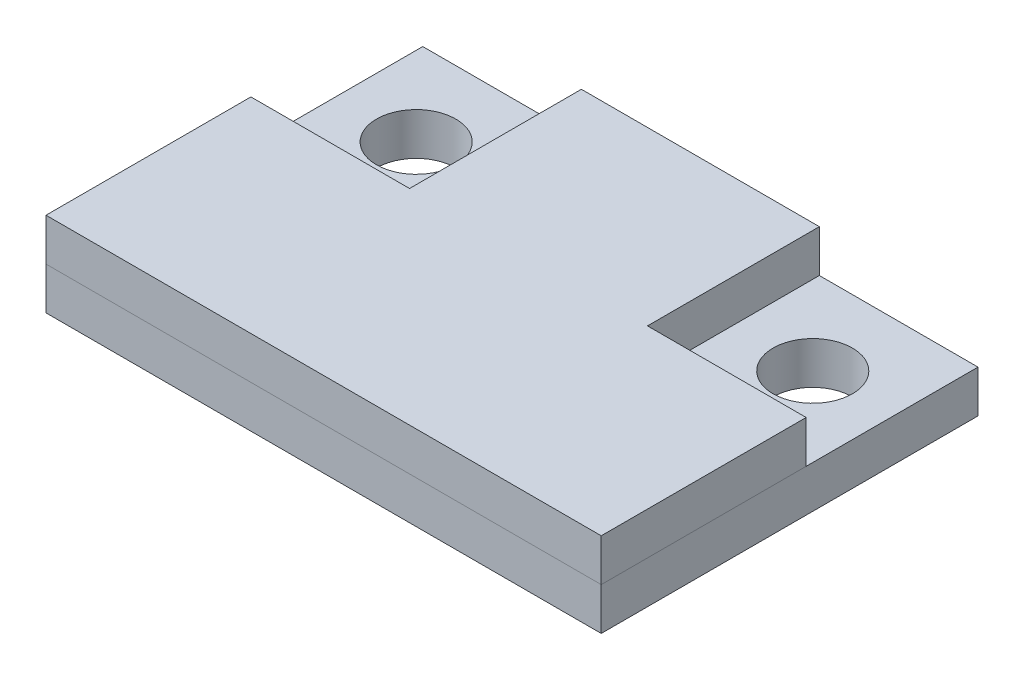
SolidWorks part; units mm, degrees
ref_plane "Front Plane" through (0, 0, 0) normal (0, 0, 1) x (1, 0, 0)
ref_plane "Top Plane" through (0, 0, 0) normal (0, 1, 0) x (1, 0, 0)
ref_plane "Right Plane" through (0, 0, 0) normal (1, 0, 0) x (0, 0, -1)
sketch "Sketch1" plane through (0, 0, 0) normal (0, 1, 0) x (1, 0, 0)
  line L0 (7.5, 3.875) -> (-7.5, 3.875) construction
  line L1 (-10.5, -7.125) -> (10.5, -7.125)
  line L2 (-10.5, -7.125) -> (-10.5, 7.125)
  line L3 (-10.5, 7.125) -> (10.5, 7.125)
  line L4 (10.5, -7.125) -> (10.5, 7.125)
  line L5 (-10.5, -7.125) -> (10.5, 7.125) construction
  line L6 (-10.5, 7.125) -> (10.5, -7.125) construction
  line L7 (0, 0) -> (0, 3.875) construction
  circle A0 centre (-7.5, 3.875) radius 1.5
  circle A1 centre (7.5, 3.875) radius 1.5
  point P0 (0, 0)
  point P9 (0, 3.875)
  dimension "D5" = 3
  dimension "D1" = 21
  dimension "D2" = 14.25
  dimension "D3" = 15
  dimension "D4" = 11
extrude "Boss-Extrude1" add sketch "Sketch1" against normal blind 1.6
sketch "Sketch2" plane through (0, 0, 0) normal (0, 1, 0) x (1, 0, 0)
  line L0 (-10.5, 7.125) -> (-4.5, 0.625) construction
  line L1 (-10.5, 7.125) -> (-4.5, 7.125) construction
  line L2 (-10.5, 7.125) -> (-10.5, 0.625) construction
  line L3 (-10.5, 0.625) -> (-4.5, 0.625)
  line L4 (-4.5, 7.125) -> (-4.5, 0.625)
  line L5 (0, 0) -> (0, 7.125) construction
  line L6 (10.5, 0.625) -> (4.5, 0.625)
  line L7 (4.5, 7.125) -> (4.5, 0.625)
  line L8 (10.5, 7.125) -> (4.5, 7.125) construction
  line L9 (10.5, 7.125) -> (10.5, 0.625) construction
  line L10 (10.5, 7.125) -> (-10.5, 7.125) construction
  line L11 (-10.5, 0.625) -> (-10.5, -7.125)
  line L12 (-10.5, -7.125) -> (10.5, -7.125)
  line L13 (10.5, -7.125) -> (10.5, 0.625)
  line L14 (4.5, 7.125) -> (-4.5, 7.125)
  point P5 (-7.5, 3.875)
extrude "Boss-Extrude2" add sketch "Sketch2" along normal blind 1.6 separate body
